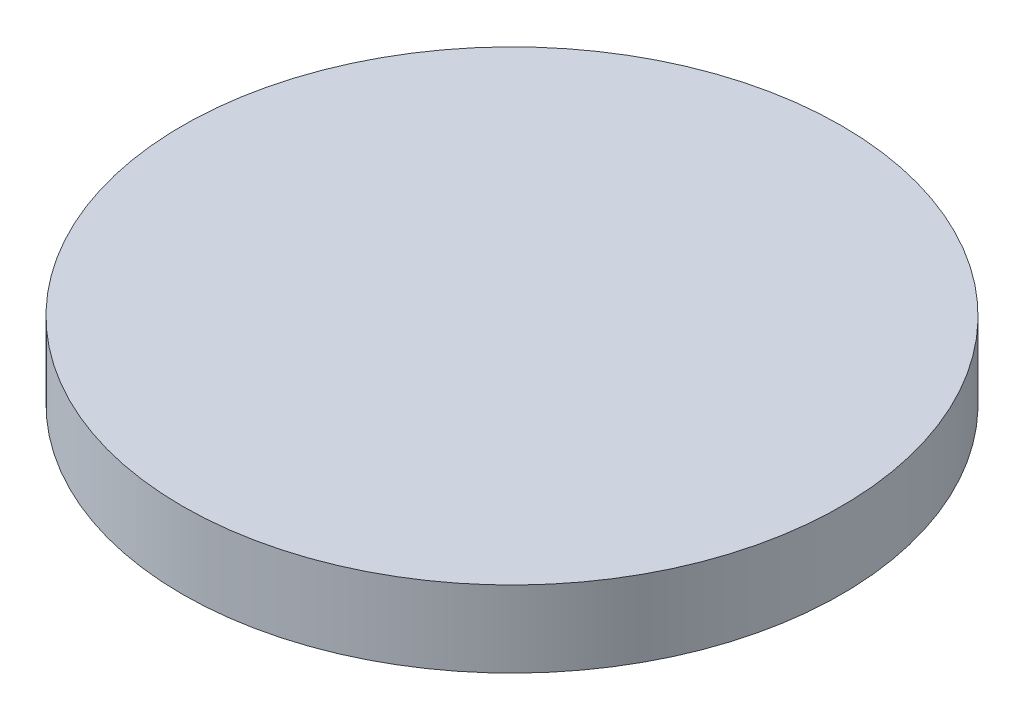
SolidWorks part; units mm, degrees
ref_plane "Спереди" through (0, 0, 0) normal (0, 0, 1) x (1, 0, 0)
ref_plane "Сверху" through (0, 0, 0) normal (0, 1, 0) x (1, 0, 0)
ref_plane "Справа" through (0, 0, 0) normal (1, 0, 0) x (0, 0, -1)
sketch "Эскиз1" plane through (0, 0, 0) normal (0, 1, 0) x (1, 0, 0)
  circle A0 centre (0, 0) radius 9.5
  dimension "D1" = 19
extrude "Бобышка-Вытянуть1" add sketch "Эскиз1" along normal blind 2.2
